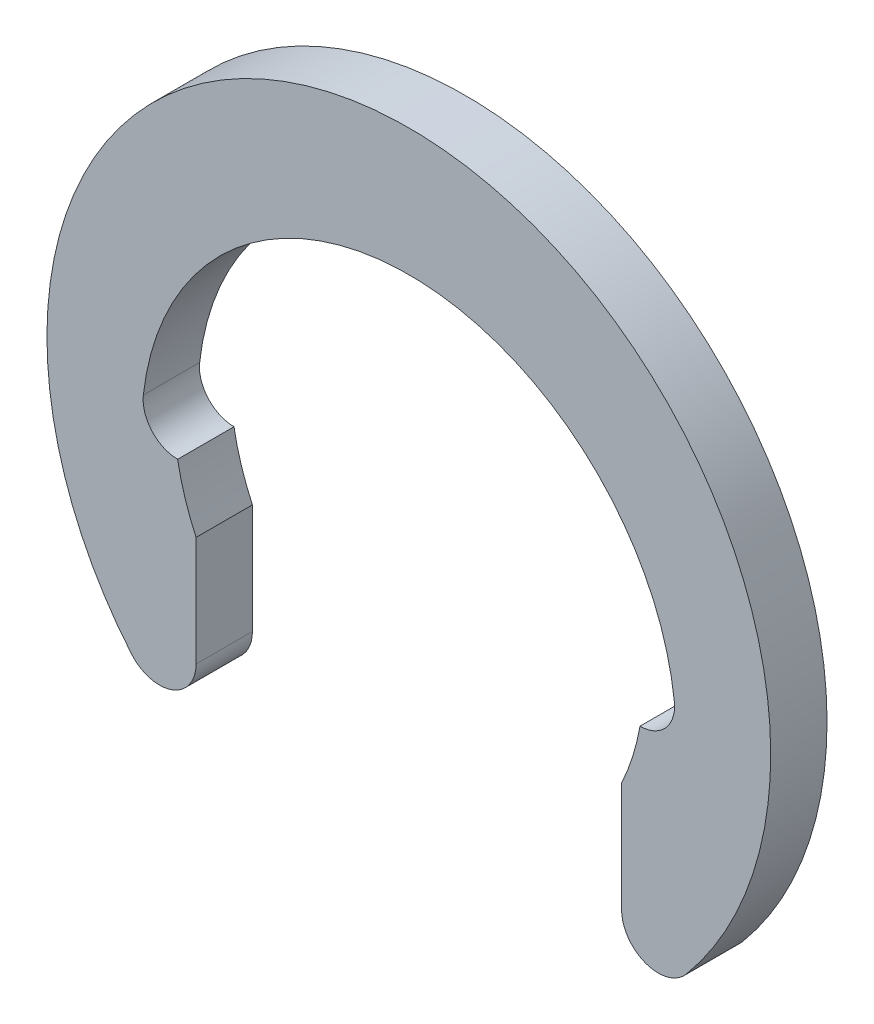
SolidWorks part; units mm, degrees
ref_plane "Plane1" through (0, 0, 0) normal (0, 0, 1) x (1, 0, 0)
ref_plane "Plane2" through (0, 0, 0) normal (0, 1, 0) x (1, 0, 0)
ref_plane "Plane3" through (0, 0, 0) normal (1, 0, 0) x (0, 0, -1)
sketch "Clipboard" plane through (0, 0, 0) normal (0, 0, 1) x (1, 0, 0)
  line L0 (0, 0) -> (1.3, 0)
  circle A0 centre (0, 0) radius 2.4
  circle A1 centre (0, 0) radius 3.7
  dimension "FreeID" = 4.8
  dimension "FreeOD" = 7.4
  dimension "LargeSection" = 1.3
sketch "BodySke" plane through (0, 0, 0) normal (0, 0, 1) x (1, 0, 0)
  line L0 (-2.825, 0) -> (2.825, 0) construction
  line L1 (0, 0) -> (0, 2.5) construction
  line L2 (0, 0) -> (2.462, -0.4341) construction
  line L3 (0, 0) -> (2.2658, -1.0565) construction
  line L4 (0, 0) -> (-2.462, -0.4341) construction
  line L5 (0, 0) -> (-2.2658, -1.0565) construction
  line L6 (2.2658, -1.0565) -> (2.2658, -2.2243)
  line L7 (-2.2658, -1.0565) -> (-2.2658, -2.2243)
  circle A0 centre (0, 0) radius 2.5 construction
  arc A1 (2.825, 0) -> (-2.825, 0) centre (0, -0.3461) ccw construction
  arc A2 (2.9548, -2.4747) -> (-2.9548, -2.4747) centre (0, 0) ccw
  arc A3 (2.2658, -1.0565) -> (2.462, -0.4341) centre (0, 0) ccw
  arc A4 (2.8279, -0.0243) -> (-2.8279, -0.0243) centre (0, -0.3461) ccw
  arc A5 (-2.462, -0.4341) -> (-2.2658, -1.0565) centre (0, 0) ccw
  arc A6 (2.462, -0.4341) -> (2.8279, -0.0243) centre (2.462, -0.0659) ccw
  arc A7 (-2.8279, -0.0243) -> (-2.462, -0.4341) centre (-2.462, -0.0659) ccw
  arc A8 (2.2658, -2.2243) -> (2.9548, -2.4747) centre (2.6558, -2.2243) ccw
  arc A9 (-2.9548, -2.4747) -> (-2.2658, -2.2243) centre (-2.6558, -2.2243) ccw
  dimension "D1" = 10
  dimension "GrooveDia" = 5
  dimension "OutsideDia" = 7.7083
  dimension "TipRad" = 0.39
  dimension "CavityWidth" = 5.65
  dimension "D2" = 15
extrude "Body" add sketch "BodySke" against normal blind 0.6
equation "' \"FreeID@Clipboard\" = 2.18"
equation "' \"Thickness@Body\" = 0.4"
equation "' \"GrooveDia@BodySke\" = 2.3"
equation "' \"FreeOD@Clipboard\" = 3.98"
equation "' \"LargeSection@Clipboard\" = 0.9"
equation "\"OutsideDia@BodySke\" = ( \"GrooveDia@BodySke\"  /  \"FreeID@Clipboard\" )  * \"FreeOD@Clipboard\""
equation "\"CavityWidth@BodySke\" = \"GrooveDia@BodySke\" + 0.25 * 2 * \"LargeSection@Clipboard\""
equation "\"TipRad@BodySke\" = 0.3 * \"LargeSection@Clipboard\""
